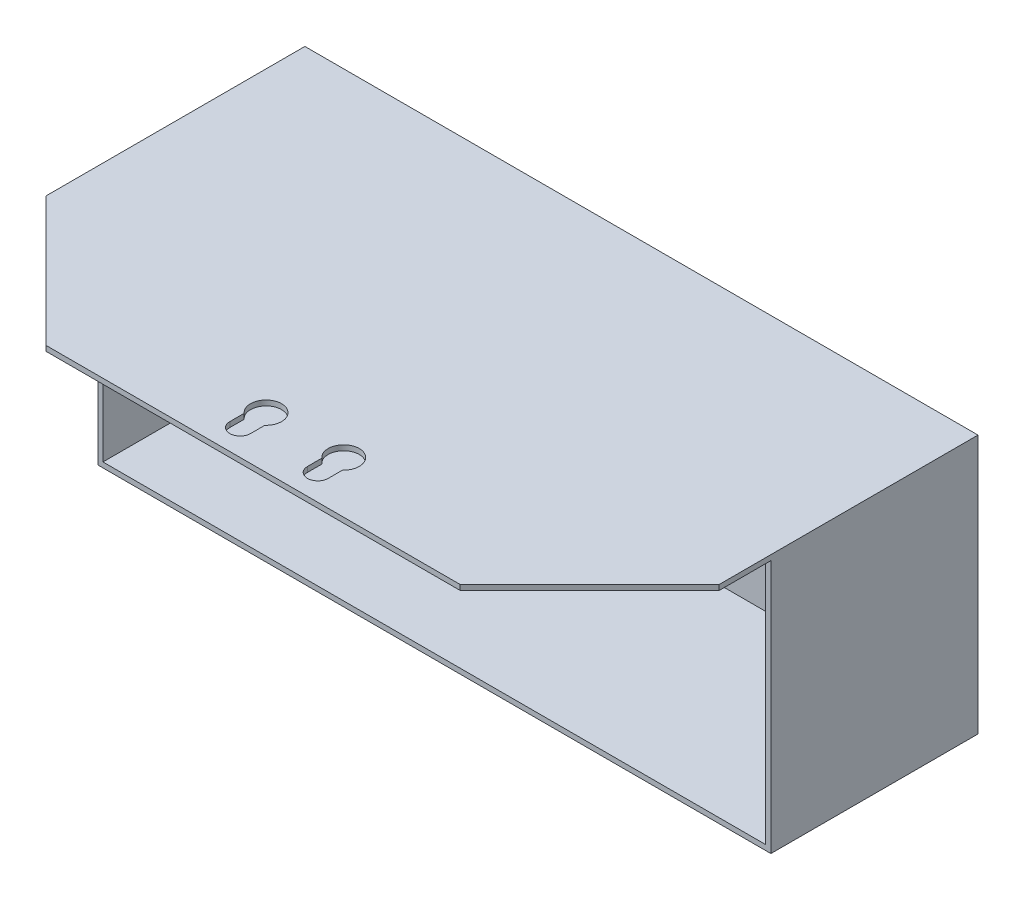
SolidWorks part; units mm, degrees
material "Q235A焊接件"
ref_plane "前视" through (0, 0, 0) normal (0, 0, 1) x (1, 0, 0)
ref_plane "上视" through (0, 0, 0) normal (0, 1, 0) x (1, 0, 0)
ref_plane "右视" through (0, 0, 0) normal (1, 0, 0) x (0, 0, -1)
sketch "草图1" plane through (0, 0, 0) normal (0, 0, 1) x (1, 0, 0)
  line L1 (0, 0) -> (260, 0)
  line L2 (0, 0) -> (0, 100)
  line L3 (0, 100) -> (260, 100)
  line L4 (260, 0) -> (260, 100)
  dimension "D1" = 100
  dimension "D2" = 260
extrude "拉伸1" add sketch "草图1" along normal blind 80
shell "抽壳1" thickness 2
sketch "草图2" plane through (260, 0, 0) normal (1, 0, 0) x (0, 0, -1)
  line L0 (-80, 0) -> (-80, 100) construction
  line L1 (-80, 98) -> (-50, 98)
  line L2 (-80, 98) -> (-80, 0)
  line L3 (-80, 0) -> (-50, 0)
  line L4 (-50, 98) -> (-50, 0)
  line L5 (-80, 0) -> (0, 0) construction
  line L6 (-80, 100) -> (0, 100) construction
  dimension "D1" = 2
  dimension "D2" = 30
extrude "切除-拉伸1" [suppressed] cut sketch "草图2" against normal through all
sketch "草图3" plane through (0, 100, 0) normal (0, 1, 0) x (1, 0, 0)
  line L1 (220, -55.5849) -> (220, -71.7125) construction
  line L2 (216, -72) -> (216, -66.4721)
  line L4 (224, -72) -> (224, -66.4721)
  line L5 (130, -80) -> (130, 0) construction
  line L6 (260, -80) -> (0, -80) construction
  line L7 (260, 0) -> (0, 0) construction
  arc A0 (224, -66.4721) -> (216, -66.4721) centre (220, -62) ccw
  arc A1 (216, -72) -> (224, -72) centre (220, -72) ccw
  dimension "D1" = 8
  dimension "D2" = 12
  dimension "D3" = 10
  dimension "D4" = 90
  dimension "D5" = 8
extrude "切除-拉伸2" [suppressed] cut sketch "草图3" against normal blind 10
pattern_linear "阵列(线性)1" [suppressed] count 2 spacing 80
sketch "草图4" plane through (0, 100, 0) normal (0, 1, 0) x (1, 0, 0)
  line L0 (260, -80) -> (260, 0) construction
  line L1 (0, -80) -> (260, -80)
  line L2 (0, -80) -> (0, -150)
  line L3 (0, -150) -> (260, -150)
  line L4 (260, -80) -> (260, -150)
  dimension "D1" = 70
extrude "凸台-拉伸1" add sketch "草图4" against normal up to surface (2 mm away) up to face at (130, 98, 41)
sketch "草图5" plane through (0, 98, 0) normal (0, -1, 0) x (-1, 0, 0)
  line L0 (-145, -120.7829) -> (-145, -136.9106) construction
  line L1 (-115, -121.1922) -> (-115, -136.9106) construction
  line L2 (-119, -140) -> (-119, -134.4721)
  line L3 (-149, -140) -> (-149, -134.4721)
  line L4 (-111, -140) -> (-111, -134.4721)
  line L5 (-141, -140) -> (-141, -134.4721)
  line L8 (-130, -150) -> (-130, 0) construction
  line L9 (0, -150) -> (-260, -150) construction
  line L10 (0, 0) -> (-260, 0) construction
  arc A0 (-111, -134.4721) -> (-119, -134.4721) centre (-115, -130) ccw
  arc A1 (-119, -140) -> (-111, -140) centre (-115, -140) ccw
  arc A2 (-141, -134.4721) -> (-149, -134.4721) centre (-145, -130) ccw
  arc A3 (-149, -140) -> (-141, -140) centre (-145, -140) ccw
  dimension "D1" = 8
  dimension "D2" = 12
  dimension "D3" = 10
  dimension "D4" = 8
  dimension "D5" = 12
  dimension "D7" = 30
  dimension "D8" = 10
  dimension "D6" = 10
extrude "切除-拉伸3" cut sketch "草图5" against normal blind 10
chamfer "倒角1" distance 50 angle 45 2 edges at (260, 99, 150) (0, 99, 150)
